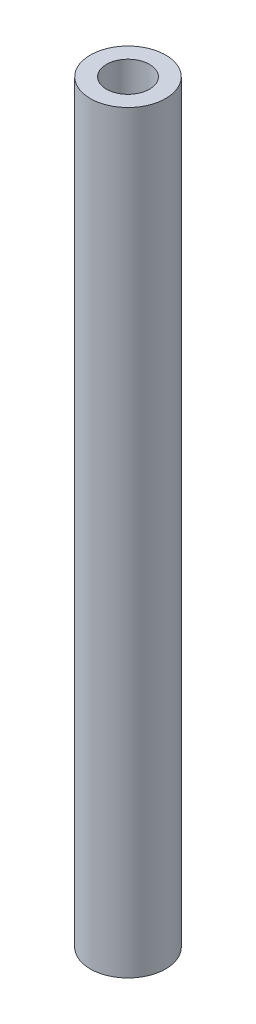
SolidWorks part; units mm, degrees
ref_plane "前视基准面" through (0, 0, 0) normal (0, 0, 1) x (1, 0, 0)
ref_plane "上视基准面" through (0, 0, 0) normal (0, 1, 0) x (1, 0, 0)
ref_plane "右视基准面" through (0, 0, 0) normal (1, 0, 0) x (0, 0, -1)
other "Configuration Table"
sketch "草图1" plane through (0, 0, 0) normal (0, 1, 0) x (1, 0, 0)
  circle A0 centre (0, 0) radius 1.75
  circle A1 centre (0, 0) radius 1
  dimension "D1" = 3.5
  dimension "D2" = 2
extrude "凸台-拉伸1" add sketch "草图1" along normal blind 35
